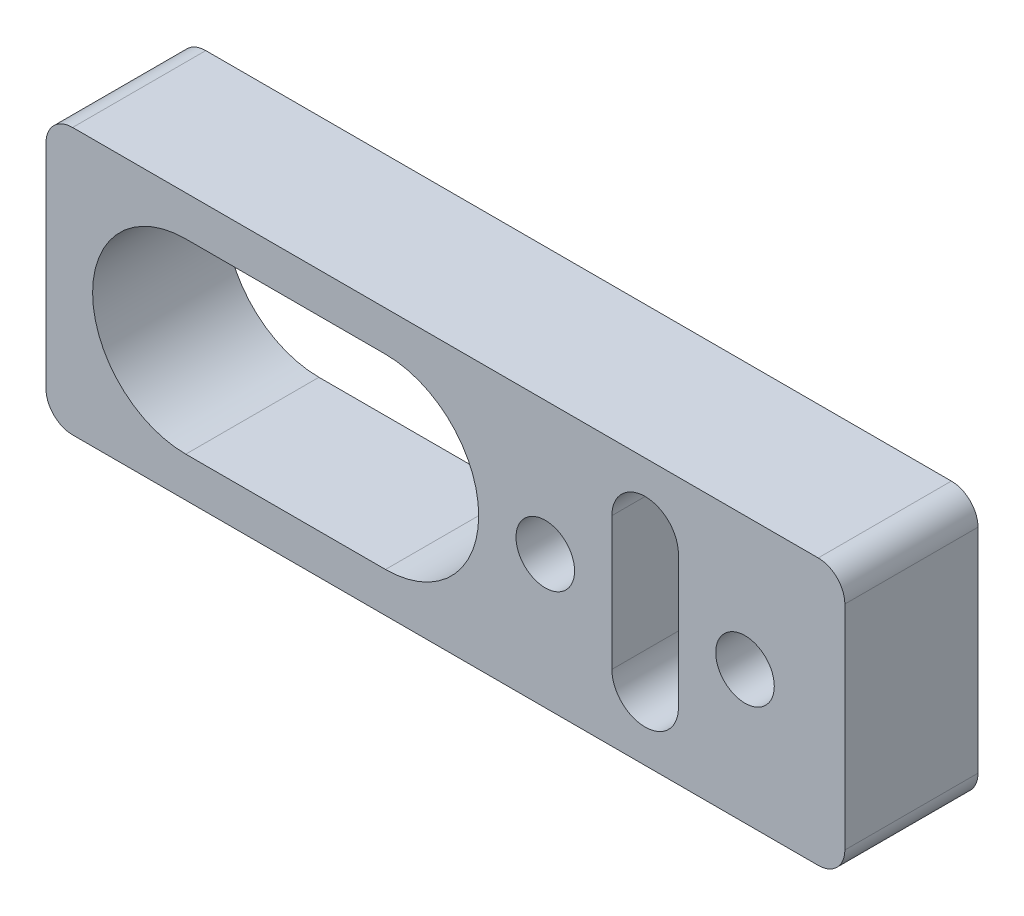
SolidWorks part; units mm, degrees
ref_plane "前视基准面" through (0, 0, 0) normal (0, 0, 1) x (1, 0, 0)
ref_plane "上视基准面" through (0, 0, 0) normal (0, 1, 0) x (1, 0, 0)
ref_plane "右视基准面" through (0, 0, 0) normal (1, 0, 0) x (0, 0, -1)
sketch "草图1" plane through (0, 0, 0) normal (0, 0, 1) x (1, 0, 0)
  line L1 (-30, -10) -> (30, -10)
  line L2 (-30, -10) -> (-30, 10)
  line L3 (-30, 10) -> (30, 10)
  line L4 (30, -10) -> (30, 10)
  line L5 (-30, -10) -> (30, 10) construction
  line L6 (-30, 10) -> (30, -10) construction
  point P0 (0, 0)
  dimension "D1" = 20
  dimension "D2" = 60
extrude "凸台-拉伸1" add sketch "草图1" along normal blind 10
fillet "圆角1" radius 2 4 edges at (30, 10, 5) (30, -10, 5) (-30, -10, 5) (-30, 10, 5)
sketch "草图2" plane through (0, 0, 10) normal (0, 0, 1) x (1, 0, 0)
  line L0 (0, 0) -> (50000, 0) construction
  line L1 (30, -8) -> (30, 8) construction
  circle A0 centre (22.5, 0) radius 2.2
  circle A1 centre (7.5, 0) radius 2.2
  dimension "D1" = 4.4
  dimension "D2" = 4.4
  dimension "D3" = 7.5
  dimension "D4" = 15
extrude "切除-拉伸1" cut sketch "草图2" against normal through all
sketch "草图3" plane through (0, 0, 10) normal (0, 0, 1) x (1, 0, 0)
  line L0 (-19.5, 0) -> (-4.5, 0) construction
  line L1 (-19.5, 7) -> (-4.5, 7)
  line L2 (-19.5, -7) -> (-4.5, -7)
  line L3 (15, -5) -> (15, 5) construction
  line L6 (12.5, -5) -> (12.5, 5)
  line L7 (17.5, -5) -> (17.5, 5)
  line L8 (7.5, 0) -> (22.5, 0) construction
  arc A0 (-19.5, 7) -> (-19.5, -7) centre (-19.5, 0) ccw
  arc A1 (-4.5, -7) -> (-4.5, 7) centre (-4.5, 0) ccw
  arc A4 (12.5, -5) -> (17.5, -5) centre (15, -5) ccw
  arc A5 (17.5, 5) -> (12.5, 5) centre (15, 5) ccw
  point P3 (-12, 0)
  point P10 (15, 0)
  dimension "D1" = 7
  dimension "D5" = 2.5
  dimension "D2" = 15
  dimension "D3" = 12
  dimension "D4" = 10
extrude "切除-拉伸2" cut sketch "草图3" against normal through all
